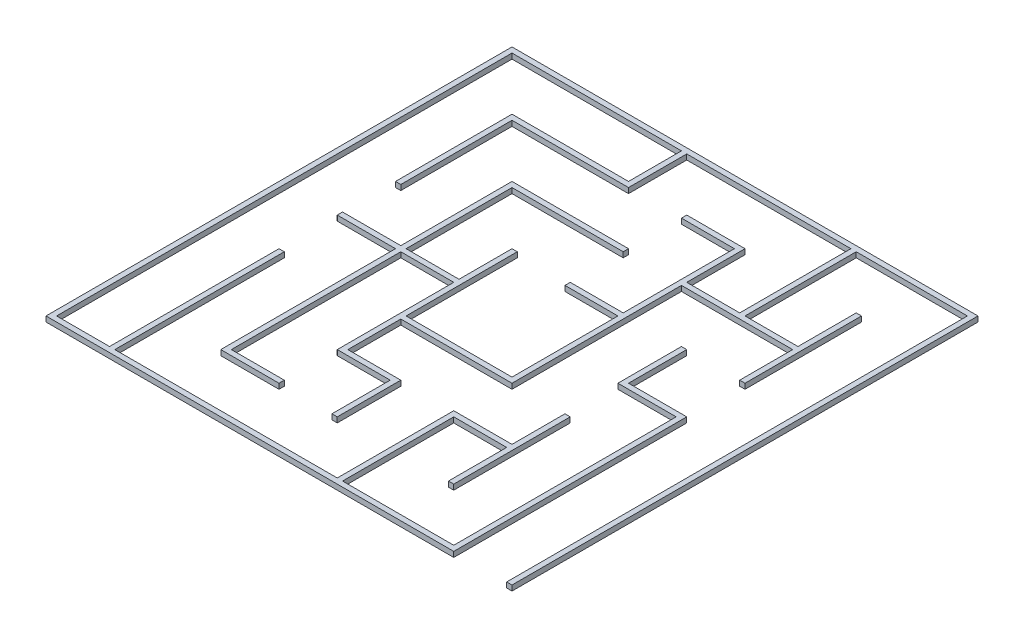
SolidWorks part; units mm, degrees
material "ABS"
ref_plane "Front Plane" through (0, 0, 0) normal (0, 0, 1) x (1, 0, 0)
ref_plane "Top Plane" through (0, 0, 0) normal (0, 1, 0) x (1, 0, 0)
ref_plane "Right Plane" through (0, 0, 0) normal (1, 0, 0) x (0, 0, -1)
sketch "Sketch1" plane through (0, 0, 0) normal (0, 1, 0) x (1, 0, 0)
  line L0 (2200, -2000) -> (2200, 4200)
  line L1 (-2000, -2000) -> (2000, -2000)
  line L2 (-2000, -2000) -> (-2000, 2000)
  line L3 (0, 2000) -> (2000, 2000)
  line L4 (2000, -2000) -> (2000, 2000)
  line L5 (-2000, -2000) -> (2000, 2000) construction
  line L6 (-2000, 2000) -> (2000, -2000) construction
  line L7 (2000, 2200) -> (0, 2200)
  line L8 (0, 2200) -> (0, 2000)
  line L9 (-2000, 2000) -> (-2000, 2200)
  line L10 (-2000, 2200) -> (-2200, 2200)
  line L11 (-2200, 2200) -> (-2200, 200)
  line L12 (-2000, -2200) -> (2200, -2200)
  line L13 (2200, -2200) -> (2200, -2000)
  line L14 (6400, 6600) -> (6400, 4400)
  line L15 (-4400, 4400) -> (0, 4400)
  line L16 (0, 9999.9863) -> (0, -7195.3613) construction
  line L17 (-8561.7108, 0) -> (-4400, 0) construction
  line L18 (0, 4200) -> (-4200, 4200)
  line L19 (2200, 4400) -> (4200, 4400)
  line L20 (0, 4400) -> (0, 4200)
  line L21 (-4200, 4200) -> (-4200, 200)
  line L22 (-4200, 0) -> (-2200, 0)
  line L23 (-4200, 200) -> (-2200, 200)
  line L24 (-2200, 0) -> (-2200, -2200)
  line L25 (-4400, 4400) -> (-4400, 200)
  line L26 (-4200, 0) -> (-4200, -6400)
  line L27 (-6400, 6400) -> (-6400, 2200)
  line L28 (-6600, 6400) -> (-6600, 2200)
  line L29 (-4400, 200) -> (-6400, 200)
  line L30 (-4400, 0) -> (-6400, 0)
  line L31 (-4400, 0) -> (-4400, -6600)
  line L32 (-4200, 0) -> (14564.4395, 0) construction
  line L33 (-2200, 6600) -> (-2200, 8600)
  line L34 (-8600, 8600) -> (-8600, -8600)
  line L35 (-6400, 2200) -> (-6600, 2200)
  line L36 (-6600, -2200) -> (-6600, -8600)
  line L37 (-6400, 0) -> (-6600, 0)
  line L38 (-6400, 200) -> (-6600, 200)
  line L39 (-6600, 200) -> (-6600, 0)
  line L40 (-6400, -2200) -> (-6600, -2200)
  line L41 (-6400, -2200) -> (-6400, -8600)
  line L42 (-8800, 8800) -> (-8800, -8800)
  line L43 (-2200, -2200) -> (-2200, -4400)
  line L44 (-2200, -6400) -> (-2200, -6600)
  line L45 (-8800, -8800) -> (6600, -8800)
  line L46 (-6400, -8600) -> (2000, -8600)
  line L47 (-8600, -8600) -> (-6600, -8600)
  line L48 (-2000, -4200) -> (0, -4200)
  line L49 (-2200, -4400) -> (-200, -4400)
  line L50 (-4200, -6400) -> (-2200, -6400)
  line L51 (-4400, -6600) -> (-2200, -6600)
  line L52 (4400, 0) -> (6400, 0)
  line L53 (4200, -6600) -> (4400, -6600)
  line L54 (-2000, -2000) -> (-2000, -4200)
  line L55 (-200, -4400) -> (-200, -6600)
  line L56 (0, -4200) -> (0, -6600)
  line L57 (2200, -4400) -> (4200, -4400)
  line L58 (4400, 8600) -> (8600, 8600)
  line L59 (2000, -4200) -> (2000, -8600)
  line L60 (-200, -6600) -> (0, -6600)
  line L61 (2000, -4200) -> (4200, -4200)
  line L62 (2200, -8600) -> (6400, -8600)
  line L63 (2200, -4400) -> (2200, -8600)
  line L64 (6400, 2200) -> (6600, 2200)
  line L65 (4400, 8600) -> (4400, 4400)
  line L66 (4400, -6400) -> (4400, -6600)
  line L67 (4200, -6600) -> (4200, -4400)
  line L68 (4200, -4200) -> (4200, -2200)
  line L69 (4400, -200) -> (6400, -200)
  line L70 (4400, -2200) -> (4400, -6400)
  line L71 (4200, -2200) -> (4400, -2200)
  line L72 (4200, 0) -> (4200, 2200)
  line L73 (8600, 8600) -> (8600, -8800)
  line L74 (8800, 8800) -> (8800, -8800)
  line L75 (6600, 0) -> (6600, -8800)
  line L77 (8600, -8800) -> (8800, -8800)
  line L79 (-8600, 8600) -> (-2200, 8600)
  line L80 (-8800, 8800) -> (8800, 8800)
  line L81 (-2000, 6600) -> (-2000, 8600)
  line L82 (-2000, 8600) -> (4200, 8600)
  line L83 (-6400, 6400) -> (-2000, 6400)
  line L84 (-6600, 6400) -> (-6600, 6600)
  line L85 (-6600, 6600) -> (-2200, 6600)
  line L86 (-2000, 6600) -> (-2000, 6400)
  line L87 (0, 6600) -> (2200, 6600)
  line L88 (0, 6400) -> (2000, 6400)
  line L89 (0, 6600) -> (0, 6400)
  line L90 (2000, 6400) -> (2000, 2200)
  line L91 (6600, 6600) -> (6600, 2200)
  line L92 (2200, 4200) -> (6400, 4200)
  line L93 (2200, 4400) -> (2200, 6600)
  line L94 (6400, 6600) -> (6600, 6600)
  line L95 (6400, -200) -> (6400, -8600)
  line L96 (6400, 0) -> (6600, 0)
  line L97 (4400, 2200) -> (4400, 0)
  line L98 (4400, 2200) -> (4200, 2200)
  line L99 (4200, 4400) -> (4200, 8600)
  line L100 (4400, 4400) -> (6400, 4400)
  line L101 (6400, 4200) -> (6400, 2200)
  line L102 (4400, -200) -> (4200, -200)
  line L103 (4200, -200) -> (4200, 0)
  point P0 (0, 0)
  dimension "D1" = 4000
  dimension "D2" = 4000
  dimension "D3" = 200
  dimension "D4" = 200
  dimension "D5" = 200
  dimension "D6" = 200
  dimension "D9" = 2000
  dimension "D10" = 200
  dimension "D11" = 200
  dimension "D12" = 2000
  dimension "D13" = 200
  dimension "D14" = 2000
  dimension "D15" = 200
  dimension "D16" = 200
  dimension "D18" = 200
  dimension "D19" = 2000
  dimension "D21" = 200
  dimension "D23" = 200
  dimension "D27" = 200
extrude "Boss-Extrude1" add sketch "Sketch1" along normal blind 200 contours L55 L60 L56 L48 L54 L2 L9 L10 L11 L23 L21 L18 L20 L15 L25 L29 L38 L39 L37 L30 L31 L51 L44 L50 L26 L22 L24 L43 L49 | L103 L102 L69 L95 L62 L63 L57 L67 L53 L66 L70 L71 L68 L61 L59 L46 L41 L40 L36 L47 L34 L79 L33 L85 L84 L28 L35 L27 L83 L86 L81 L82 L99 L19 L93 L87 L89 L88 L90 L7 L8 L3 L4 L1 L54 L12 L13 L0 L92 L101 L64
sketch3d "URDF Reference"
  line L0 (0, 0, 0) -> (10, 0, 0) construction
  line L1 (0, 0, 0) -> (0, 0, -10) construction
  point P0 (0, 0, 0)
  point P1 (0, 0, 0)
